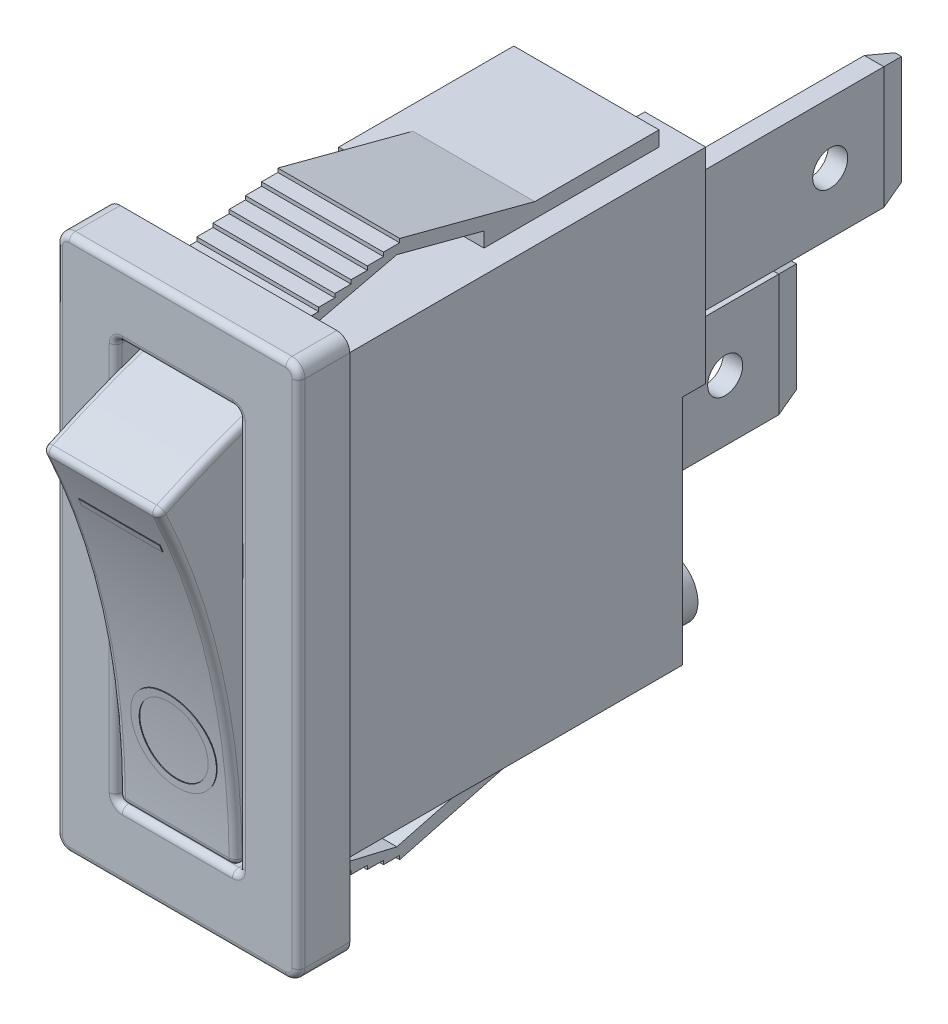
SolidWorks part; units mm, degrees
ref_plane "Front" through (0, 0, 0) normal (0, 0, 1) x (1, 0, 0)
ref_plane "Top" through (0, 0, 0) normal (0, 1, 0) x (1, 0, 0)
ref_plane "Right" through (0, 0, 0) normal (1, 0, 0) x (0, 0, -1)
sketch "Sketch3" plane through (0, 0, 0) normal (1, 0, 0) x (0, 0, -1)
  line L0 (0, 8.5598) -> (0, -8.5598)
  line L1 (0, 8.5598) -> (7.62, 8.5598)
  line L2 (7.62, 8.5598) -> (7.62, 9.144)
  line L3 (7.62, 9.144) -> (14.478, 9.144)
  line L4 (14.478, 9.144) -> (14.478, -9.144)
  line L5 (0, 0) -> (14.478, 0) construction
  line L6 (7.62, -9.144) -> (14.478, -9.144)
  line L7 (7.62, -8.5598) -> (7.62, -9.144)
  line L8 (0, -8.5598) -> (7.62, -8.5598)
  dimension "D1" = 17.1196
  dimension "D2" = 18.288
  dimension "D3" = 6.858
  dimension "D4" = 14.478
extrude "Extrude1" add sketch "Sketch3" along normal mid plane 6.604
sketch "Sketch4" plane through (0, 0, 0) normal (1, 0, 0) x (0, 0, -1)
  line L0 (0, 0) -> (14.478, 0) construction
  line L1 (0, 8.5598) -> (0, -8.5598) construction
  line L2 (14.478, -9.144) -> (14.478, 9.144) construction
  line L3 (7.62, 9.144) -> (4.2064, 10.0451)
  line L4 (4.2064, 10.0451) -> (0, 9.0553)
  line L5 (0, 9.0553) -> (0, 9.525)
  line L6 (0, 9.525) -> (0.508, 9.6445)
  line L7 (4.318, 10.541) -> (9.6104, 9.144)
  line L8 (7.62, 9.144) -> (9.6104, 9.144)
  line L9 (14.478, 9.144) -> (7.62, 9.144) construction
  line L10 (4.318, 10.541) -> (4.318, 10.3916)
  line L11 (4.318, 10.3916) -> (3.683, 10.3916)
  line L12 (3.683, 10.3916) -> (3.683, 10.2422)
  line L13 (3.683, 10.2422) -> (3.048, 10.2422)
  line L14 (3.048, 10.2422) -> (3.048, 10.0928)
  line L15 (3.048, 10.0928) -> (2.413, 10.0928)
  line L16 (2.413, 10.0928) -> (2.413, 9.9434)
  line L17 (2.413, 9.9434) -> (1.778, 9.9434)
  line L18 (1.778, 9.9434) -> (1.778, 9.7939)
  line L19 (1.778, 9.7939) -> (1.143, 9.7939)
  line L20 (1.143, 9.7939) -> (1.143, 9.6445)
  line L21 (1.143, 9.6445) -> (0.508, 9.6445)
  line L22 (0.508, 9.6445) -> (4.318, 10.541) construction
  line L23 (7.62, 9.144) -> (7.62, 8.5598) construction
  line L24 (0.508, -9.6445) -> (4.318, -10.541) construction
  line L25 (1.143, -9.6445) -> (0.508, -9.6445)
  line L26 (1.143, -9.7939) -> (1.143, -9.6445)
  line L27 (1.778, -9.7939) -> (1.143, -9.7939)
  line L28 (1.778, -9.9434) -> (1.778, -9.7939)
  line L29 (2.413, -9.9434) -> (1.778, -9.9434)
  line L30 (2.413, -10.0928) -> (2.413, -9.9434)
  line L31 (3.048, -10.0928) -> (2.413, -10.0928)
  line L32 (3.048, -10.2422) -> (3.048, -10.0928)
  line L33 (3.683, -10.2422) -> (3.048, -10.2422)
  line L34 (3.683, -10.3916) -> (3.683, -10.2422)
  line L35 (4.318, -10.3916) -> (3.683, -10.3916)
  line L36 (4.318, -10.541) -> (4.318, -10.3916)
  line L37 (7.62, -9.144) -> (9.6104, -9.144)
  line L38 (4.318, -10.541) -> (9.6104, -9.144)
  line L39 (0, -9.525) -> (0.508, -9.6445)
  line L40 (0, -9.0553) -> (0, -9.525)
  line L41 (4.2064, -10.0451) -> (0, -9.0553)
  line L42 (7.62, -9.144) -> (4.2064, -10.0451)
  dimension "D1" = 0.508
  dimension "D2" = 0.1494
  dimension "D3" = 0.635
  dimension "D4" = 3.302
  dimension "D5" = 21.082
  dimension "D6" = 0.4572
  dimension "D7" = 19.05
extrude "Extrude2" add sketch "Sketch4" along normal mid plane 4.7752
sketch "Sketch5" plane through (0, 0, 0) normal (0, 0, 1) x (1, 0, 0)
  line L1 (3.302, 8.5598) -> (-3.302, 8.5598) construction
  line L2 (3.302, 9.144) -> (2.3876, 9.144)
  line L3 (3.302, 9.144) -> (3.302, 8.5598)
  line L4 (3.302, 8.5598) -> (2.3876, 8.5598)
  line L6 (2.3876, 9.144) -> (2.3876, 8.5598)
  line L7 (2.3876, 9.525) -> (2.3876, 9.0553) construction
  line L8 (0, 0) -> (4.256, 0) construction
  line L9 (2.3876, -9.144) -> (2.3876, -8.5598)
  line L10 (3.302, -8.5598) -> (2.3876, -8.5598)
  line L11 (3.302, -9.144) -> (3.302, -8.5598)
  line L12 (3.302, -9.144) -> (2.3876, -9.144)
extrude "Extrude3" cut sketch "Sketch5" against normal through all
sketch "Sketch6" plane through (0, 0, 0) normal (0, 0, 1) x (1, 0, 0)
  line L1 (4.7498, 10.5029) -> (-4.7498, 10.5029)
  line L2 (4.7498, 10.5029) -> (4.7498, -10.5029)
  line L3 (4.7498, -10.5029) -> (-4.7498, -10.5029)
  line L4 (-4.7498, 10.5029) -> (-4.7498, -10.5029)
  line L5 (4.7498, 10.5029) -> (-4.7498, -10.5029) construction
  line L6 (4.7498, -10.5029) -> (-4.7498, 10.5029) construction
  line L7 (-2.413, 7.874) -> (2.413, 7.874)
  line L8 (-2.413, 7.874) -> (-2.413, -7.874)
  line L9 (-2.413, -7.874) -> (2.413, -7.874)
  line L10 (2.413, 7.874) -> (2.413, -7.874)
  line L11 (-2.413, 7.874) -> (2.413, -7.874) construction
  line L12 (-2.413, -7.874) -> (2.413, 7.874) construction
  point P0 (0, 0)
  point P6 (0, 0)
  dimension "D1" = 21.0058
  dimension "D2" = 9.4996
  dimension "D3" = 4.826
  dimension "D4" = 15.748
extrude "Extrude4" add sketch "Sketch6" along normal blind 2.0066
fillet "Fillet1" radius 0.508 4 edges at (-4.7498, 10.5029, 1.0033) (-4.7498, -10.5029, 1.0033) (4.7498, -10.5029, 1.0033) (4.7498, 10.5029, 1.0033)
fillet "Fillet2" radius 0.254 16 edges at (0, 7.874, 2.0066) (-2.413, 0, 2.0066) (0, -7.874, 2.0066) (2.413, 0, 2.0066) (4.601, 10.3541, 2.0066) (4.7498, 0, 2.0066) (4.601, -10.3541, 2.0066) (0, -10.5029, 2.0066) (-4.601, -10.3541, 2.0066) (-4.7498, 0, 2.0066) (-4.601, 10.3541, 2.0066) (0, 10.5029, 2.0066) (-2.413, -7.874, 1.0033) (2.413, -7.874, 1.0033) (2.413, 7.874, 1.0033) (-2.413, 7.874, 1.0033)
sketch "Sketch8" plane through (0, 0, -14.478) normal (0, 0, -1) x (-1, 0, 0)
  line L0 (-3.302, -8.5598) -> (-3.302, 8.5598) construction
  line L1 (-3.302, -8.5598) -> (3.302, -8.5598) construction
  line L2 (-0.9144, 2.8448) -> (-0.9144, 0.5334)
  line L3 (0.9144, -0.5334) -> (3.302, -0.5334)
  line L4 (0.9144, -0.5334) -> (0.9144, -2.8448)
  line L5 (0.9144, -8.5598) -> (3.302, -8.5598)
  line L6 (3.302, -0.5334) -> (3.302, -8.5598)
  line L7 (0.9144, -2.8448) -> (2.4384, -2.8448)
  line L9 (0.9144, -6.2484) -> (2.4384, -6.2484)
  line L10 (2.4384, -2.8448) -> (2.4384, -6.2484)
  line L11 (-3.302, 8.5598) -> (-0.9144, 8.5598)
  line L12 (-3.302, 8.5598) -> (-3.302, 0.5334)
  line L13 (-3.302, 0.5334) -> (-0.9144, 0.5334)
  line L14 (-0.9144, 8.5598) -> (-0.9144, 6.2484)
  line L15 (-0.9144, 6.2484) -> (-2.4384, 6.2484)
  line L16 (0.9144, -6.2484) -> (0.9144, -8.5598)
  line L17 (-0.9144, 2.8448) -> (-2.4384, 2.8448)
  line L18 (-2.4384, 6.2484) -> (-2.4384, 2.8448)
  line L19 (3.302, -9.144) -> (3.302, 9.144) construction
  circle A0 centre (-1.778, -7.0358) radius 1.2192
  dimension "D1" = 2.4384
  dimension "D3" = 1.524
  dimension "D2" = 1.524
  dimension "D4" = 8.0264
  dimension "D5" = 3.4036
  dimension "D6" = 1.524
  dimension "D7" = 2.3876
extrude "Extrude6" add sketch "Sketch8" along normal blind 0.9144
sketch "Sketch9" plane through (0, 0, -14.478) normal (0, 0, -1) x (-1, 0, 0)
  line L1 (-2.4384, 6.9342) -> (-1.6764, 6.9342)
  line L2 (-2.4384, 6.9342) -> (-2.4384, 2.159)
  line L3 (-2.4384, 2.159) -> (-1.6764, 2.159)
  line L4 (-1.6764, 6.9342) -> (-1.6764, 2.159)
  line L6 (2.4384, -2.159) -> (1.6764, -2.159)
  line L7 (2.4384, -2.159) -> (2.4384, -6.9342)
  line L8 (2.4384, -6.9342) -> (1.6764, -6.9342)
  line L9 (1.6764, -2.159) -> (1.6764, -6.9342)
  line L10 (-0.9144, 6.2484) -> (-0.9144, 2.8448) construction
  line L11 (-0.9144, 2.8448) -> (-0.9144, 4.5466) construction
  line L12 (-0.9144, 4.5466) -> (-1.6764, 4.5466) construction
  line L13 (-2.4384, 2.8448) -> (-2.4384, 6.2484) construction
  line L14 (0.9144, -2.8448) -> (0.9144, -6.2484) construction
  line L15 (0.9144, -4.5466) -> (1.6764, -4.5466) construction
  line L16 (2.4384, -2.8448) -> (2.4384, -6.2484) construction
  dimension "D1" = 0.762
  dimension "D2" = 4.7752
extrude "Extrude7" add sketch "Sketch9" along normal blind 9.7028 separate body
sketch "Sketch10" plane through (2.4384, 0, 0) normal (1, 0, 0) x (0, 0, -1)
  line L0 (24.1808, 4.5466) -> (21.1328, 4.5466) construction
  line L1 (24.1808, 6.9342) -> (24.1808, 2.159) construction
  line L2 (24.1808, -4.5466) -> (21.1328, -4.5466) construction
  line L3 (24.1808, -2.159) -> (24.1808, -6.9342) construction
  circle A0 centre (21.1328, 4.5466) radius 0.6858
  circle A1 centre (21.1328, -4.5466) radius 0.6858
  dimension "D1" = 3.048
  dimension "D2" = 1.3716
extrude "Extrude8" cut sketch "Sketch10" against normal through all
chamfer "Chamfer1" distance 0.254 angle 75 4 edges at (1.6764, 4.5466, -24.1808) (2.4384, 4.5466, -24.1808) (2.0574, 6.9342, -24.1808) (2.0574, 2.159, -24.1808)
chamfer "Chamfer2" distance 0.254 angle 75 4 edges at (-2.0574, -2.159, -24.1808) (-2.4384, -4.5466, -24.1808) (-2.0574, -6.9342, -24.1808) (-1.6764, -4.5466, -24.1808)
sketch "Sketch7" plane through (0, 0, 0) normal (1, 0, 0) x (0, 0, -1)
  line L0 (0, 0) -> (0.762, 0) construction
  line L1 (0, -9.9949) -> (0, 9.9949) construction
  line L2 (-2.0066, -10.5029) -> (-2.0066, 10.5029) construction
  line L3 (-2.0066, -7.874) -> (0, -7.874) construction
  line L4 (0, 7.747) -> (-4.2283, 7.747) construction
  line L5 (-2.0066, 7.874) -> (0, 7.874) construction
  line L6 (-2.7846, -0.8051) -> (0.762, 0) construction
  line L7 (-5.08, 5.7924) -> (-9.0397, 3.8971) construction
  line L8 (3.4194, -7.3167) -> (0, 7.747)
  arc A0 (-2.0066, -7.747) -> (-5.08, 5.7924) centre (-33.3663, -7.747) ccw
  arc A2 (-5.08, 5.7924) -> (0, 7.747) centre (9.7848, -25.2628) cw
  arc A3 (-2.0066, -7.747) -> (3.4194, -7.3167) centre (-2.0066, 26.6825) ccw
  dimension "D1" = 0.762
  dimension "D2" = 0.127
  dimension "D3" = 0.127
  dimension "D4" = 5.08
extrude "Extrude5" add sketch "Sketch7" along normal mid plane 4.572 separate body
fillet "Fillet3" radius 0.254 8 edges at (0, 5.7924, 5.08) (2.286, -0.8051, 2.7846) (0, -7.747, 2.0066) (-2.286, -0.8051, 2.7846) (-2.286, -7.6393, -0.7149) (2.286, -7.6393, -0.7149) (2.286, 6.8703, 2.5787) (-2.286, 6.8703, 2.5787)
ref_plane "Plane1" through (0, -0.8006, 3.527) normal (0, -0.2214, 0.9752) x (1, 0, 0)
surface "Surface-Offset1" parameters "D1"=0.0254
sketch "Sketch12" plane through (0, -0.8006, 3.527) normal (0, -0.2214, 0.9752) x (1, 0, 0)
  line L0 (1.651, 6.5264) -> (1.651, -6.8638) construction
  line L1 (2.032, 6.5264) -> (-2.032, 6.5264) construction
  line L2 (-2.032, -6.8638) -> (2.032, -6.8638) construction
  line L3 (2.032, -6.8638) -> (2.032, 6.5264) construction
  text T0 "O     I" font "Century Gothic" height 3.175
  dimension "D1" = 0.381
extrude "Extrude9" add sketch "Sketch12" along normal up to surface (2.2616 mm away) from offset 2.54 offset against normal yes
